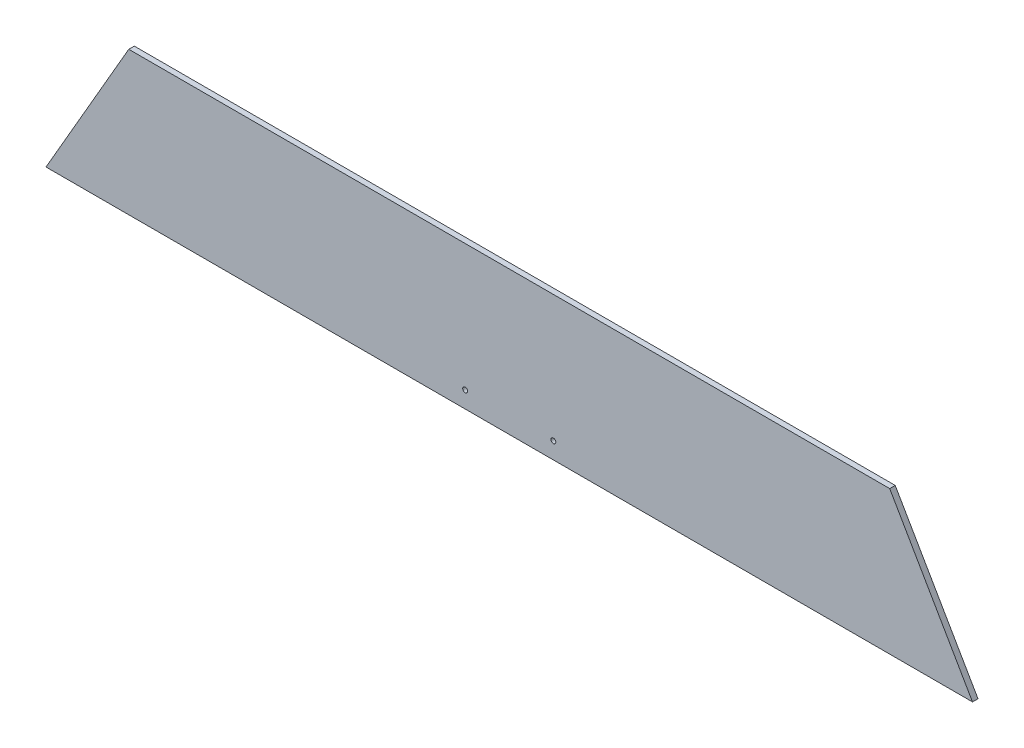
SolidWorks part; units mm, degrees
material "Beech"
ref_plane "Front Plane" through (0, 0, 0) normal (0, 0, 1) x (1, 0, 0)
ref_plane "Top Plane" through (0, 0, 0) normal (0, 1, 0) x (1, 0, 0)
ref_plane "Right Plane" through (0, 0, 0) normal (1, 0, 0) x (0, 0, -1)
sketch "Sketch1" plane through (0, 0, 0) normal (0, 0, 1) x (1, 0, 0)
  line L1 (-533.4705, 0) -> (533.4705, 0)
  line L2 (-533.4705, 0) -> (-438.15, 165.1)
  line L3 (-438.15, 165.1) -> (438.15, 165.1)
  line L4 (533.4705, 0) -> (438.15, 165.1)
  point P5 (0, 165.1)
  point P6 (-505.9852, 0)
  dimension "D1" = 165.1
  dimension "D2" = 60
  dimension "D3" = 876.3
extrude "Boss-Extrude1" add sketch "Sketch1" along normal blind 6.35
hole_wizard "#10 Clearance Hole1" positions "Sketch3" profile "Sketch4" hole size "#10" standard "ANSI Inch" end condition through all
sketch "Sketch3" plane through (0, 0, 6.35) normal (0, 0, 1) x (1, 0, 0)
  line L0 (-50.8, 19.05) -> (50.8, 19.05) construction
  point P0 (-50.8, 19.05)
  point P2 (50.8, 19.05)
  point P8 (0, 19.05)
  dimension "D1" = 19.05
  dimension "D2" = 101.6
sketch "Sketch4" plane through (-50.8, 19.05, 6.35) normal (1, 0, 0) x (0, -1, 0)
  line L0 (0, 0) -> (0, 6.35)
  line L1 (0, 6.35) -> (2.8067, 6.35)
  line L2 (2.8067, 6.35) -> (2.8067, 0)
  line L5 (2.8067, 0) -> (0, 0)
  line L11 (0, -6.35) -> (0, 107.95) construction
  dimension "Thru Hole Dia." = 5.6134
  dimension "Thru Hole Depth" = 6.35
